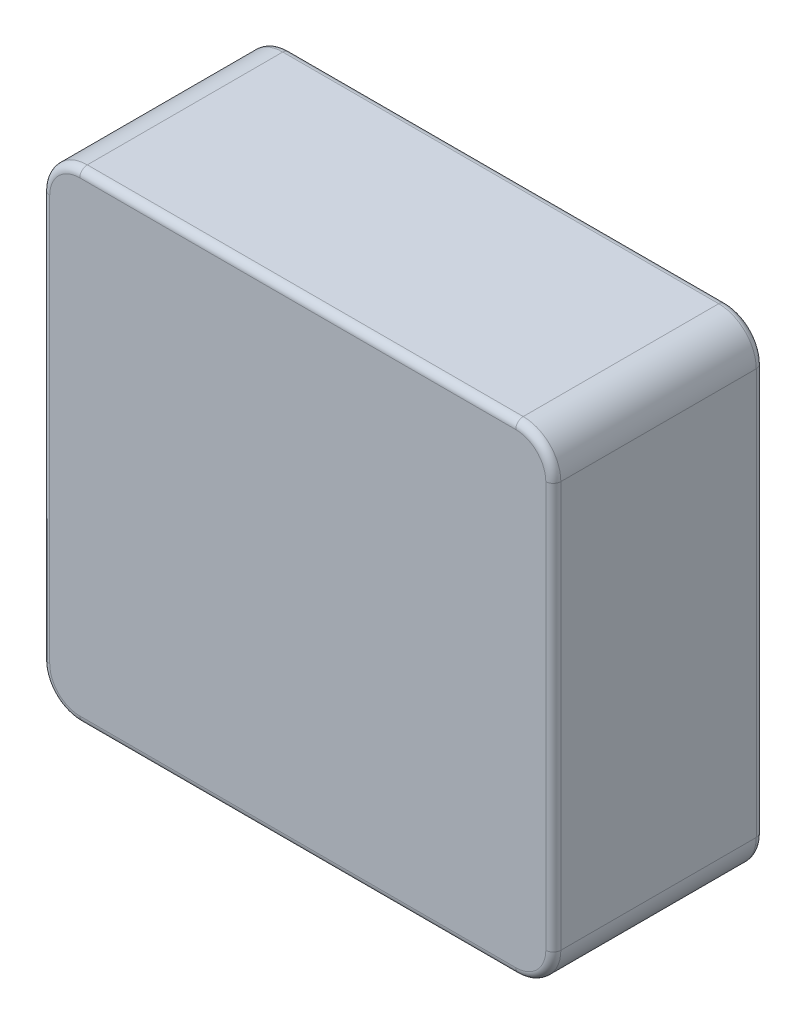
SolidWorks part; units mm, degrees
ref_plane "Front Plane" through (0, 0, 0) normal (0, 0, 1) x (1, 0, 0)
ref_plane "Top Plane" through (0, 0, 0) normal (0, 1, 0) x (1, 0, 0)
ref_plane "Right Plane" through (0, 0, 0) normal (1, 0, 0) x (0, 0, -1)
sketch "Sketch1" plane through (0, 0, 0) normal (0, 0, 1) x (1, 0, 0)
  line L1 (-2.9, -3.2) -> (2.9, -3.2)
  line L2 (-3.4, -2.7) -> (-3.4, 2.7)
  line L3 (-2.9, 3.2) -> (2.9, 3.2)
  line L4 (3.4, -2.7) -> (3.4, 2.7)
  line L5 (-3.4, -3.2) -> (3.4, 3.2) construction
  line L6 (-3.4, 3.2) -> (3.4, -3.2) construction
  arc A0 (2.9, -3.2) -> (3.4, -2.7) centre (2.9, -2.7) ccw
  arc A1 (2.9, 3.2) -> (3.4, 2.7) centre (2.9, 2.7) cw
  arc A2 (-3.4, 2.7) -> (-2.9, 3.2) centre (-2.9, 2.7) cw
  arc A3 (-2.9, -3.2) -> (-3.4, -2.7) centre (-2.9, -2.7) cw
  point P0 (0, 0)
  dimension "D3" = 0.5
  dimension "D1" = 6.4
  dimension "D2" = 6.8
extrude "Boss-Extrude1" add sketch "Sketch1" along normal blind 2.8
sketch "Sketch2" plane through (0, 0, 0) normal (0, 0, -1) x (-1, 0, 0)
  line L1 (-2.525, 2.7) -> (2.525, 2.7)
  line L2 (-2.525, 2.7) -> (-2.525, 1.3)
  line L3 (-2.525, 1.3) -> (2.525, 1.3)
  line L4 (2.525, 2.7) -> (2.525, 1.3)
  line L5 (-2.525, -1.3) -> (2.525, -1.3)
  line L6 (-2.525, -1.3) -> (-2.525, -2.7)
  line L7 (-2.525, -2.7) -> (2.525, -2.7)
  line L8 (2.525, -1.3) -> (2.525, -2.7)
  point P8 (0, 1.3)
  point P10 (0, -1.3)
  point P11 (-0.261, 0.9797)
  point P12 (0, -2.7)
  point P13 (0, 2.7)
  dimension "D1" = 1.4
  dimension "D2" = 1.4
  dimension "D3" = 1.3
  dimension "D4" = 1.3
  dimension "D5" = 5.05
extrude "Boss-Extrude2" add sketch "Sketch2" along normal blind 0.1
fillet "Fillet1" radius 0.1 16 edges at (3.2536, -3.0536, 0) (0, -3.2, 0) (-3.2536, -3.0536, 0) (-3.4, 0, 0) (-3.2536, 3.0536, 0) (0, 3.2, 0) (3.2536, 3.0536, 0) (0, -3.2, 2.8) (-3.2536, -3.0536, 2.8) (-3.4, 0, 2.8) (-3.2536, 3.0536, 2.8) (0, 3.2, 2.8) (3.2536, 3.0536, 2.8) (3.4, 0, 2.8) (3.2536, -3.0536, 2.8) (3.4, 0, 0)
